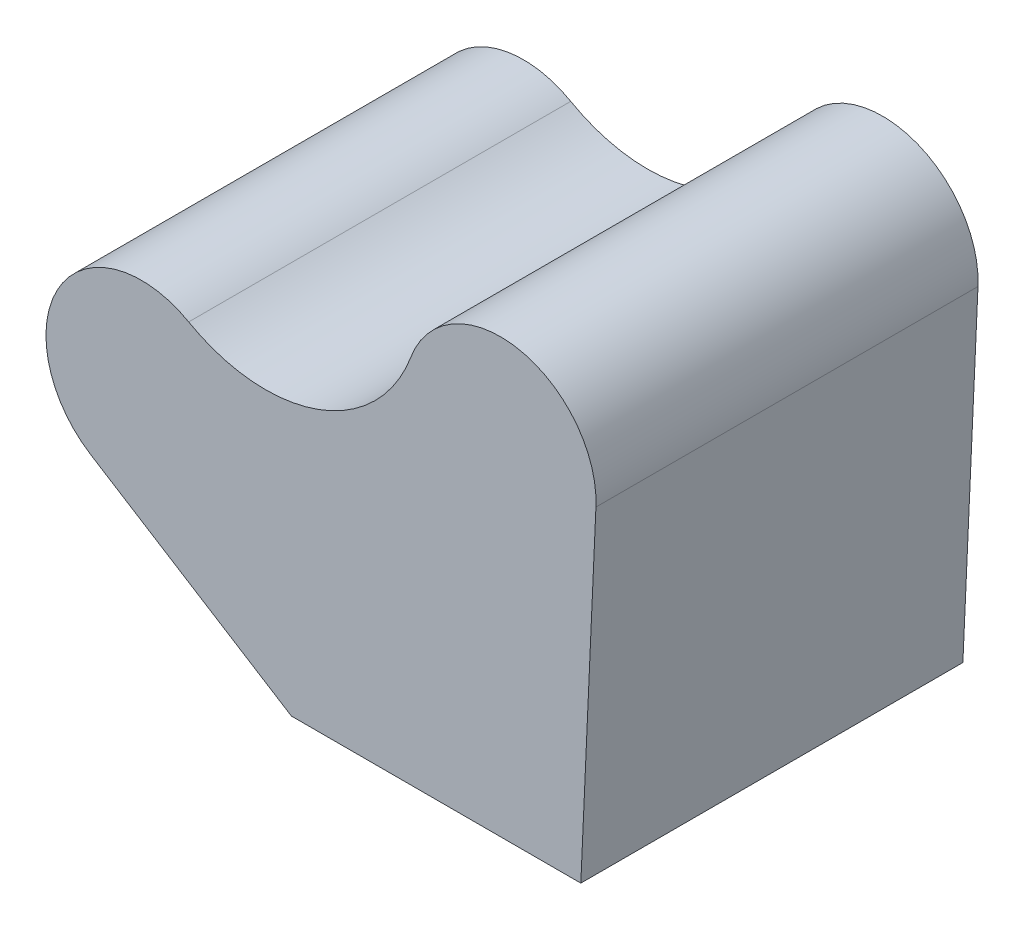
SolidWorks part; units mm, degrees
ref_plane "前视基准面" through (0, 0, 0) normal (0, 0, 1) x (1, 0, 0)
ref_plane "上视基准面" through (0, 0, 0) normal (0, 1, 0) x (1, 0, 0)
ref_plane "右视基准面" through (0, 0, 0) normal (1, 0, 0) x (0, 0, -1)
sketch "草图1" plane through (0, 0, 0) normal (0, 0, 1) x (1, 0, 0)
  line L0 (47.5774, 13.2278) -> (45.9953, -21.6627)
  line L1 (-5.3186, -8.4683) -> (15.6895, -21.6627)
  line L2 (15.6895, -21.6627) -> (45.9953, -21.6627)
  line L3 (37.5877, 13.6808) -> (0, 0)
  arc A0 (-5.3186, -8.4683) -> (4.9405, 8.6944) centre (0, 0) cw
  arc A1 (28.2145, 17.1654) -> (47.5774, 13.2278) centre (37.5877, 13.6808) cw
  arc A2 (4.9405, 8.6944) -> (28.2145, 17.1654) centre (12.9736, 22.8313) ccw
  dimension "D2" = 10
  dimension "D1" = 40
  dimension "D3" = 20
extrude "凸台-拉伸1" add sketch "草图1" along normal mid plane 40 contours A2 A1 L0 L2 L1 A0
